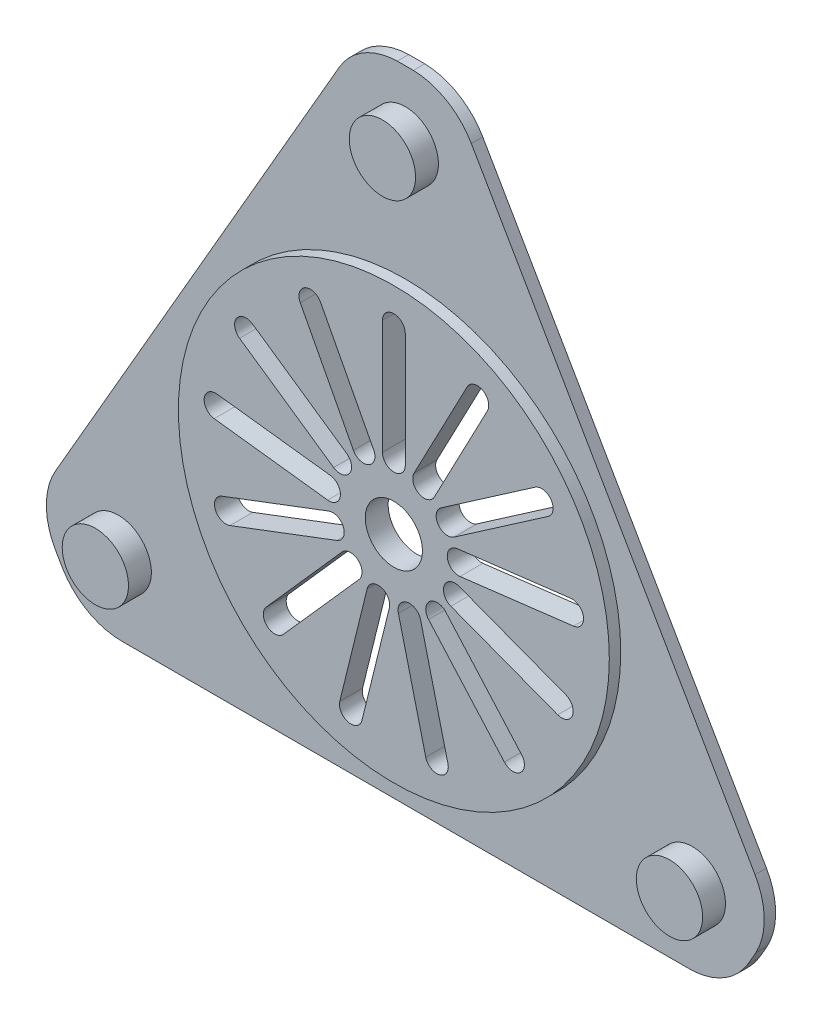
SolidWorks part; units mm, degrees
ref_plane "Спереди" through (0, 0, 0) normal (0, 0, 1) x (1, 0, 0)
ref_plane "Сверху" through (0, 0, 0) normal (0, 1, 0) x (1, 0, 0)
ref_plane "Справа" through (0, 0, 0) normal (1, 0, 0) x (0, 0, -1)
sketch "Sketch1" plane through (0, 0, 0) normal (0, 0, 1) x (1, 0, 0)
  line L0 (3.9, 6.755) -> (7.8, 0) construction
  line L2 (5.85, 10.1325) -> (11.7, 0) construction
  line L4 (7.8, 13.51) -> (15.6, 0) construction
  circle A61 centre (0, 0) radius 20
  circle A131 centre (0, 0) radius 1.25
  circle A484 centre (3.9, 0) radius 1.25
  circle A485 centre (7.8, 0) radius 1.25
  circle A486 centre (11.7, 0) radius 1.25
  circle A487 centre (15.6, 0) radius 1.25
  circle A488 centre (1.95, -3.3775) radius 1.25
  circle A489 centre (3.9, -6.755) radius 1.25
  circle A490 centre (5.85, -10.1325) radius 1.25
  circle A491 centre (7.8, -13.51) radius 1.25
  circle A492 centre (-1.95, -3.3775) radius 1.25
  circle A493 centre (-3.9, -6.755) radius 1.25
  circle A494 centre (-5.85, -10.1325) radius 1.25
  circle A495 centre (-7.8, -13.51) radius 1.25
  circle A496 centre (-3.9, 0) radius 1.25
  circle A497 centre (-7.8, 0) radius 1.25
  circle A498 centre (-11.7, 0) radius 1.25
  circle A499 centre (-15.6, 0) radius 1.25
  circle A500 centre (-1.95, 3.3775) radius 1.25
  circle A501 centre (-3.9, 6.755) radius 1.25
  circle A502 centre (-5.85, 10.1325) radius 1.25
  circle A503 centre (-7.8, 13.51) radius 1.25
  circle A504 centre (1.95, 3.3775) radius 1.25
  circle A505 centre (3.9, 6.755) radius 1.25
  circle A506 centre (5.85, 10.1325) radius 1.25
  circle A507 centre (7.8, 13.51) radius 1.25
  circle A508 centre (5.85, 3.3775) radius 1.25
  circle A509 centre (7.8, 6.755) radius 1.25
  circle A510 centre (9.75, 3.3775) radius 1.25
  circle A511 centre (11.7, 6.755) radius 1.25
  circle A512 centre (9.7491, 10.1341) radius 1.25
  circle A513 centre (13.6509, 3.3759) radius 1.25
  circle A514 centre (5.85, -3.3791) radius 1.25
  circle A515 centre (9.75, -3.3791) radius 1.25
  circle A516 centre (7.8, -6.7566) radius 1.25
  circle A517 centre (11.7, -6.7566) radius 1.25
  circle A518 centre (9.7491, -10.1356) radius 1.25
  circle A519 centre (13.6509, -3.3775) radius 1.25
  circle A520 centre (-0.0013, -6.7573) radius 1.25
  circle A521 centre (1.9487, -10.1348) radius 1.25
  circle A522 centre (-1.9513, -10.1348) radius 1.25
  circle A523 centre (-0.0013, -13.5123) radius 1.25
  circle A524 centre (-3.9032, -13.5123) radius 1.25
  circle A525 centre (3.9005, -13.5123) radius 1.25
  circle A526 centre (-5.8527, -3.3791) radius 1.25
  circle A527 centre (-7.8027, -6.7566) radius 1.25
  circle A528 centre (-9.7527, -3.3791) radius 1.25
  circle A529 centre (-11.7027, -6.7566) radius 1.25
  circle A530 centre (-13.6536, -3.3775) radius 1.25
  circle A531 centre (-9.7518, -10.1356) radius 1.25
  circle A532 centre (-5.8527, 3.3775) radius 1.25
  circle A533 centre (-9.7527, 3.3775) radius 1.25
  circle A534 centre (-7.8027, 6.755) radius 1.25
  circle A535 centre (-11.7027, 6.755) radius 1.25
  circle A536 centre (-9.7518, 10.1341) radius 1.25
  circle A537 centre (-13.6536, 3.3759) radius 1.25
  circle A538 centre (-0.0014, 6.7558) radius 1.25
  circle A539 centre (-1.9514, 10.1333) radius 1.25
  circle A540 centre (1.9486, 10.1333) radius 1.25
  circle A541 centre (-0.0014, 13.5108) radius 1.25
  circle A542 centre (3.9005, 13.5108) radius 1.25
  circle A543 centre (-3.9032, 13.5108) radius 1.25
  circle A544 centre (13.65, -1.1258) radius 2.2517 construction
  circle A545 centre (11.7009, -4.5044) radius 2.2522 construction
  circle A546 centre (9.75, -7.8834) radius 2.2522 construction
  circle A547 centre (7.7987, -11.2591) radius 2.2509 construction
  circle A548 centre (13.65, -1.1258) radius 0.65
  circle A549 centre (11.7009, -4.5044) radius 0.65
  circle A550 centre (9.75, -7.8834) radius 0.65
  circle A551 centre (7.7987, -11.2591) radius 0.65
  circle A552 centre (9.75, -1.1258) radius 0.65
  circle A553 centre (7.8009, -4.5044) radius 0.65
  circle A554 centre (5.85, -7.8834) radius 0.65
  circle A555 centre (3.8987, -11.2591) radius 0.65
  circle A556 centre (5.85, -1.1258) radius 0.65
  circle A557 centre (3.9009, -4.5044) radius 0.65
  circle A558 centre (1.95, -7.8834) radius 0.65
  circle A559 centre (-0.0013, -11.2591) radius 0.65
  circle A560 centre (1.95, -1.1258) radius 0.65
  circle A561 centre (0.0009, -4.5044) radius 0.65
  circle A562 centre (-1.95, -7.8834) radius 0.65
  circle A563 centre (-3.9013, -11.2591) radius 0.65
  circle A564 centre (-1.95, -1.1258) radius 0.65
  circle A565 centre (-3.8991, -4.5044) radius 0.65
  circle A566 centre (-5.85, -7.8834) radius 0.65
  circle A567 centre (-7.8013, -11.2591) radius 0.65
  circle A568 centre (-5.85, -1.1258) radius 0.65
  circle A569 centre (-7.7991, -4.5044) radius 0.65
  circle A570 centre (-9.75, -7.8834) radius 0.65
  circle A572 centre (-9.75, -1.1258) radius 0.65
  circle A573 centre (-11.6991, -4.5044) radius 0.65
  circle A576 centre (-13.65, -1.1258) radius 0.65
  circle A587 centre (0, 2.2517) radius 2.2517 construction
  circle A588 centre (0, 2.2517) radius 0.65
  circle A589 centre (3.9, 2.2517) radius 0.65
  circle A590 centre (7.8, 2.2517) radius 0.65
  circle A591 centre (11.7, 2.2517) radius 0.65
  circle A592 centre (15.6, 2.2517) radius 0.65
  circle A593 centre (1.9491, 5.6297) radius 2.2522 construction
  circle A594 centre (1.9491, 5.6297) radius 0.65
  circle A595 centre (5.8491, 5.6297) radius 0.65
  circle A596 centre (9.7491, 5.6297) radius 0.65
  circle A597 centre (13.6491, 5.6297) radius 0.65
  circle A598 centre (3.8991, 9.0072) radius 2.2522 construction
  circle A599 centre (3.8991, 9.0072) radius 0.65
  circle A600 centre (7.7991, 9.0072) radius 0.65
  circle A601 centre (11.6991, 9.0072) radius 0.65
  circle A602 centre (5.85, 12.3842) radius 2.2517 construction
  circle A603 centre (5.85, 12.3842) radius 0.65
  circle A604 centre (9.75, 12.3842) radius 0.65
  circle A605 centre (5.85, -14.6358) radius 0.65
  circle A606 centre (1.9509, -14.6353) radius 0.65
  circle A607 centre (-1.9491, -14.6353) radius 0.65
  circle A608 centre (-5.85, -14.6358) radius 0.65
  circle A609 centre (-15.6, 2.2517) radius 0.65
  circle A610 centre (-13.65, 5.6281) radius 0.65
  circle A611 centre (-11.7, 9.0056) radius 0.65
  circle A612 centre (-9.75, 12.3842) radius 0.65
  circle A613 centre (-5.85, 12.3842) radius 0.65
  circle A614 centre (-1.95, 12.3842) radius 0.65
  circle A615 centre (1.95, 12.3842) radius 0.65
  circle A616 centre (-7.8, 9.0056) radius 0.65
  circle A617 centre (-9.75, 5.6281) radius 0.65
  circle A618 centre (-11.7, 2.2517) radius 0.65
  circle A619 centre (-3.9, 9.0056) radius 0.65
  circle A620 centre (-5.85, 5.6281) radius 0.65
  circle A621 centre (-7.8, 2.2517) radius 0.65
  circle A622 centre (0, 9.0056) radius 0.65
  circle A623 centre (-1.95, 5.6281) radius 0.65
  circle A624 centre (-3.9, 2.2517) radius 0.65
  circle A625 centre (-15.5991, -4.5044) radius 0.65
  circle A626 centre (-13.65, -7.8834) radius 0.65
  circle A627 centre (-17.55, -7.8834) radius 0.65
  circle A628 centre (-19.5013, -11.2591) radius 0.65
  circle A629 centre (-15.6013, -11.2591) radius 0.65
  circle A630 centre (-11.7013, -11.2591) radius 0.65
  point P51 (0, 0)
  point P125 (-0.0013, -0.0008)
  point P231 (0, 0)
  dimension "D1" = 5
  dimension "D3" = 6
  dimension "D5" = 8
  dimension "D7" = 4
  dimension "D11" = 4
  dimension "D2" = 6
  dimension "D6" = 5
  dimension "D8" = 3
  dimension "D9" = 2
  dimension "D4" = 1.3
  dimension "D10" = 3
ref_plane "Plane1" through (0, 0, 10) normal (0, 0, 1) x (1, 0, 0)
sketch "Sketch2" plane through (0, 0, 10) normal (0, 0, 1) x (1, 0, 0)
  line L0 (0, 15.7117) -> (0, 5.7117) construction
  line L47 (1, 15.7117) -> (1, 5.7117)
  line L53 (-1, 15.7117) -> (-1, 5.7117)
  line L56 (6.4161, 14.3768) -> (1.7689, 5.5222)
  line L59 (8.1871, 13.4473) -> (3.5398, 4.5928)
  line L62 (7.3016, 13.912) -> (2.6544, 5.0575) construction
  line L65 (12.3624, 9.7483) -> (4.1326, 4.0676)
  line L68 (13.4986, 8.1023) -> (5.2687, 2.4216)
  line L71 (12.9305, 8.9253) -> (4.7007, 3.2446) construction
  line L86 (15.4766, 2.8865) -> (5.5495, 1.6812)
  line L89 (15.7177, 0.9011) -> (5.7906, -0.3042)
  line L92 (15.5972, 1.8938) -> (5.6701, 0.6885) construction
  line L95 (15.0453, -4.6364) -> (5.6952, -1.0904)
  line L98 (14.3361, -6.5065) -> (4.986, -2.9604)
  line L101 (14.6907, -5.5715) -> (5.3406, -2.0254) construction
  line L104 (11.1673, -11.0973) -> (4.5361, -3.6122)
  line L107 (9.6703, -12.4235) -> (3.0391, -4.9384)
  line L110 (10.4188, -11.7604) -> (3.7876, -4.2753) construction
  line L113 (4.731, -15.0159) -> (2.3378, -5.3064)
  line L116 (2.7891, -15.4945) -> (0.396, -5.7851)
  line L119 (3.7601, -15.2552) -> (1.3669, -5.5458) construction
  line L120 (-2.7891, -15.4945) -> (-0.396, -5.7851)
  line L121 (-4.731, -15.0159) -> (-2.3378, -5.3064)
  line L124 (-3.7601, -15.2552) -> (-1.3669, -5.5458) construction
  line L127 (-9.6703, -12.4235) -> (-3.0391, -4.9384)
  line L130 (-11.1673, -11.0973) -> (-4.5361, -3.6122)
  line L133 (-10.4188, -11.7604) -> (-3.7876, -4.2753) construction
  line L136 (-14.3361, -6.5065) -> (-4.986, -2.9604)
  line L139 (-15.0453, -4.6364) -> (-5.6952, -1.0904)
  line L142 (-14.6907, -5.5715) -> (-5.3406, -2.0254) construction
  line L172 (-15.7177, 0.9011) -> (-5.7906, -0.3042)
  line L173 (-15.4766, 2.8865) -> (-5.5495, 1.6812)
  line L174 (-15.5972, 1.8938) -> (-5.6701, 0.6885) construction
  line L186 (-6.3905, 14.3534) -> (-2.3232, 5.2179) construction
  line L187 (-13.4986, 8.1023) -> (-5.2687, 2.4216)
  line L188 (-12.3624, 9.7483) -> (-4.1326, 4.0676)
  line L189 (-12.9305, 8.9253) -> (-4.7007, 3.2446) construction
  line L190 (-8.1871, 13.4473) -> (-3.5398, 4.5928)
  line L191 (-6.4161, 14.3768) -> (-1.7689, 5.5222)
  line L192 (-7.3016, 13.912) -> (-2.6544, 5.0575) construction
  circle A52 centre (0, 0) radius 16.85 construction
  circle A53 centre (0, 0) radius 18.85
  arc A193 (1, 15.7117) -> (-1, 15.7117) centre (0, 15.7117) ccw
  arc A198 (-1, 5.7117) -> (1, 5.7117) centre (0, 5.7117) ccw
  circle A199 centre (0, 0) radius 2.5
  arc A201 (8.1871, 13.4473) -> (6.4161, 14.3768) centre (7.3016, 13.912) ccw
  arc A202 (1.7689, 5.5222) -> (3.5398, 4.5928) centre (2.6544, 5.0575) ccw
  arc A203 (13.4986, 8.1023) -> (12.3624, 9.7483) centre (12.9305, 8.9253) ccw
  arc A204 (4.1326, 4.0676) -> (5.2687, 2.4216) centre (4.7007, 3.2446) ccw
  arc A205 (15.7177, 0.9011) -> (15.4766, 2.8865) centre (15.5972, 1.8938) ccw
  arc A206 (5.5495, 1.6812) -> (5.7906, -0.3042) centre (5.6701, 0.6885) ccw
  arc A207 (14.3361, -6.5065) -> (15.0453, -4.6364) centre (14.6907, -5.5715) ccw
  arc A208 (5.6952, -1.0904) -> (4.986, -2.9604) centre (5.3406, -2.0254) ccw
  arc A209 (9.6703, -12.4235) -> (11.1673, -11.0973) centre (10.4188, -11.7604) ccw
  arc A210 (4.5361, -3.6122) -> (3.0391, -4.9384) centre (3.7876, -4.2753) ccw
  arc A211 (2.7891, -15.4945) -> (4.731, -15.0159) centre (3.7601, -15.2552) ccw
  arc A212 (2.3378, -5.3064) -> (0.396, -5.7851) centre (1.3669, -5.5458) ccw
  arc A213 (-4.731, -15.0159) -> (-2.7891, -15.4945) centre (-3.7601, -15.2552) ccw
  arc A214 (-0.396, -5.7851) -> (-2.3378, -5.3064) centre (-1.3669, -5.5458) ccw
  arc A215 (-11.1673, -11.0973) -> (-9.6703, -12.4235) centre (-10.4188, -11.7604) ccw
  arc A216 (-3.0391, -4.9384) -> (-4.5361, -3.6122) centre (-3.7876, -4.2753) ccw
  arc A217 (-15.0453, -4.6364) -> (-14.3361, -6.5065) centre (-14.6907, -5.5715) ccw
  arc A218 (-4.986, -2.9604) -> (-5.6952, -1.0904) centre (-5.3406, -2.0254) ccw
  arc A229 (-15.4766, 2.8865) -> (-15.7177, 0.9011) centre (-15.5972, 1.8938) ccw
  arc A230 (-5.7906, -0.3042) -> (-5.5495, 1.6812) centre (-5.6701, 0.6885) ccw
  arc A239 (-12.3624, 9.7483) -> (-13.4986, 8.1023) centre (-12.9305, 8.9253) ccw
  arc A240 (-5.2687, 2.4216) -> (-4.1326, 4.0676) centre (-4.7007, 3.2446) ccw
  arc A241 (-6.4161, 14.3768) -> (-8.1871, 13.4473) centre (-7.3016, 13.912) ccw
  arc A242 (-3.5398, 4.5928) -> (-1.7689, 5.5222) centre (-2.6544, 5.0575) ccw
  point P2 (0, 10.7117)
  point P12 (4.978, 9.4848)
  point P19 (8.8156, 6.085)
  point P26 (10.6336, 1.2912)
  point P33 (10.0156, -3.7984)
  point P40 (7.1032, -8.0178)
  point P47 (2.5635, -10.4005)
  point P54 (-2.5635, -10.4005)
  point P61 (-7.1032, -8.0178)
  point P68 (-10.0156, -3.7984)
  point P73 (0, 0)
  point P74 (0, 0)
  point P75 (-9.2766, -5.3559)
  point P76 (-10.6336, 1.2912)
  point P80 (0, 0)
  point P86 (-10.653, -1.1197)
  point P92 (-8.8156, 6.085)
  point P99 (-10.1875, 3.3101)
  point P103 (-4.3569, 9.7857)
  point P108 (0, 0)
  point P110 (-7.9604, 7.1675)
  point P112 (-4.978, 9.4848)
  point P117 (-4.3569, 9.7857)
  dimension "D1" = 2
  dimension "D2" = 10
  dimension "D3" = 13
extrude "Boss-Extrude1" add sketch "Sketch2" against normal blind 2
sketch "Sketch3" plane through (0, 0, 8) normal (0, 0, -1) x (-1, 0, 0)
  circle A0 centre (0, 0) radius 17.6
  circle A1 centre (0, 0) radius 35
extrude "Boss-Extrude2" add sketch "Sketch3" against normal blind 1
sketch "Sketch4" plane through (0, 0, 8) normal (0, 0, -1) x (-1, 0, 0)
  circle A0 centre (0, 0) radius 29 construction
  circle A1 centre (0, 29) radius 2.9
  circle A2 centre (25.1147, -14.5) radius 2.9
  circle A3 centre (-25.1147, -14.5) radius 2.9
  point P11 (0, 0)
  dimension "D1" = 3
extrude "Boss-Extrude3" add sketch "Sketch4" against normal blind 3
sketch "Sketch6" plane through (0, 0, 9) normal (0, 0, -1) x (-1, 0, 0)
  circle A0 centre (0, 30) radius 5
  circle A2 centre (25.9808, -15) radius 5
  circle A3 centre (-25.9808, -15) radius 5
  point P10 (0, 0)
  dimension "D1" = 3
extrude "Boss-Extrude4" add sketch "Sketch6" along normal blind 1
sketch "Sketch7" plane through (0, 0, 8) normal (0, 0, -1) x (-1, 0, 0)
  line L1 (0, 42) -> (-36.3731, -21)
  line L2 (-36.3731, -21) -> (36.3731, -21)
  line L3 (36.3731, -21) -> (0, 42)
  circle A2 centre (0, 0) radius 21 construction
  circle A3 centre (0, 0) radius 59.1314
extrude "Cut-Extrude1" cut sketch "Sketch7" against normal blind 10
fillet "Fillet1" radius 6 6 edges at (-32.1865, -13.7487, 8.5) (-4.1865, 34.7487, 8.5) (28, -21, 8.5) (-28, -21, 8.5) (4.1865, 34.7487, 8.5) (32.1865, -13.7487, 8.5)
